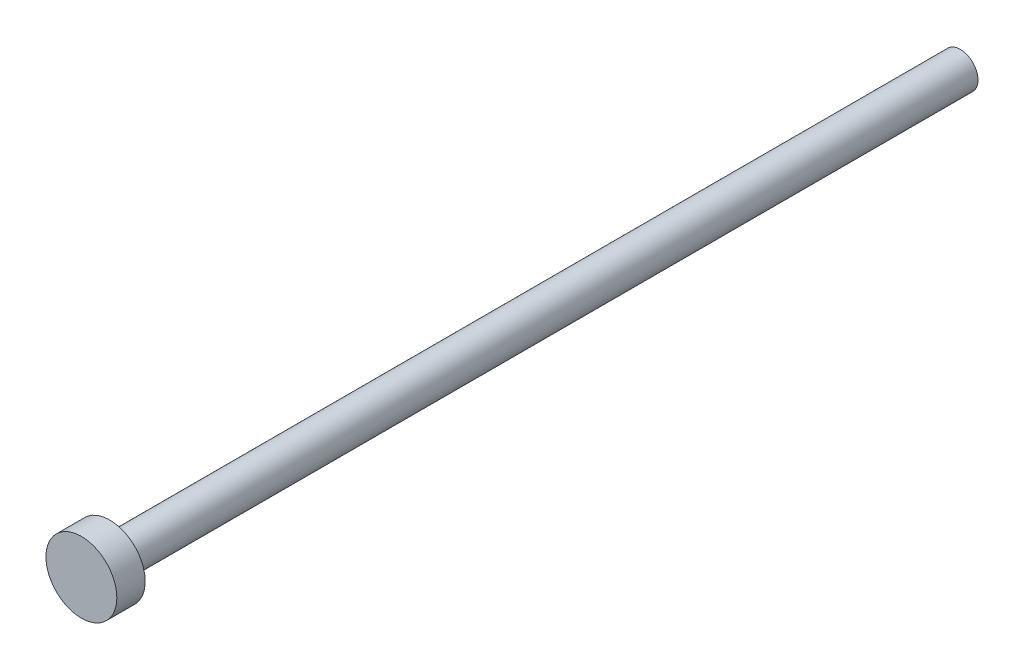
SolidWorks part; units mm, degrees
ref_plane "Front Plane" through (0, 0, 0) normal (0, 0, 1) x (1, 0, 0)
ref_plane "Top Plane" through (0, 0, 0) normal (0, 1, 0) x (1, 0, 0)
ref_plane "Right Plane" through (0, 0, 0) normal (1, 0, 0) x (0, 0, -1)
sketch "Sketch1" plane through (0, 0, 0) normal (0, 0, 1) x (1, 0, 0)
  circle A0 centre (0, 0) radius 1.25
  dimension "D1" = 2.5
extrude "Boss-Extrude1" add sketch "Sketch1" along normal blind 1
sketch "Sketch2" plane through (0, 0, 0) normal (0, 0, -1) x (-1, 0, 0)
  circle A0 centre (0, 0) radius 0.625
  dimension "D1" = 1.25
extrude "Boss-Extrude2" add sketch "Sketch2" along normal blind 30
